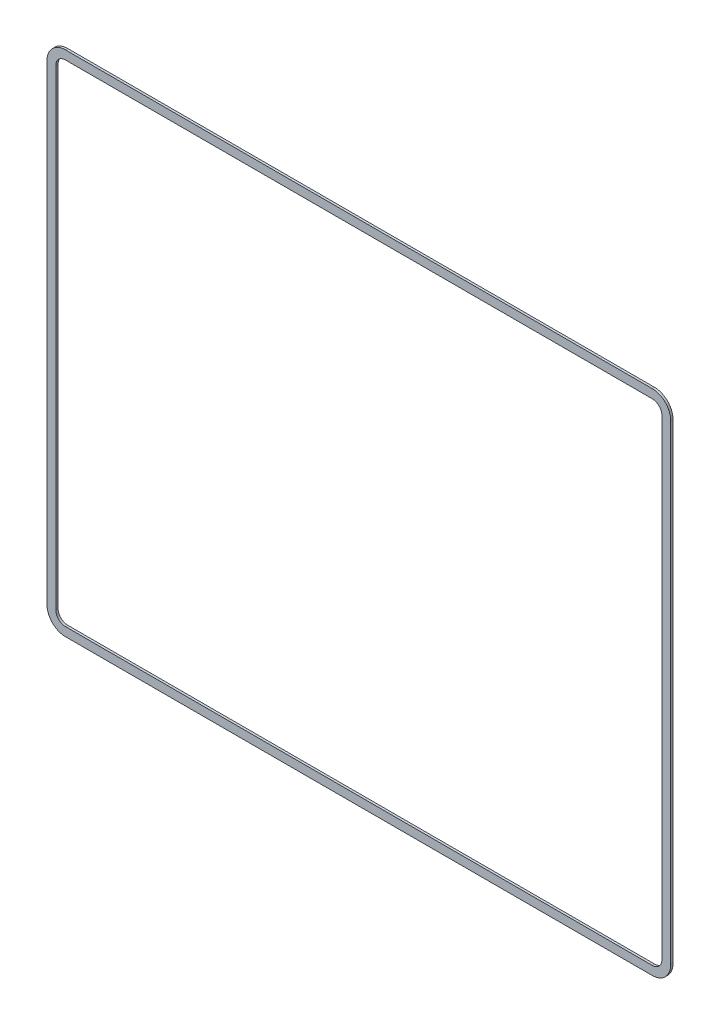
SolidWorks part; units mm, degrees
ref_plane "Front Plane" through (0, 0, 0) normal (0, 0, 1) x (1, 0, 0)
ref_plane "Top Plane" through (0, 0, 0) normal (0, 1, 0) x (1, 0, 0)
ref_plane "Right Plane" through (0, 0, 0) normal (1, 0, 0) x (0, 0, -1)
sketch "Sketch1" plane through (0, 0, 0) normal (0, 0, 1) x (-1, 0, 0)
  line L0 (-79, 0) -> (79, 0) construction
  line L3 (-65.6, 51) -> (-65.6, -51)
  line L4 (-63.5, 55) -> (63.5, 55)
  line L5 (-67.5, 51) -> (-67.5, -51)
  line L6 (-63.5, -55) -> (63.5, -55)
  line L7 (67.5, 51) -> (67.5, -51)
  line L8 (-67.5, 55) -> (67.5, -55) construction
  line L9 (-67.5, -55) -> (67.5, 55) construction
  line L10 (-63.5, -53.1) -> (63.5, -53.1)
  line L11 (65.6, 51) -> (65.6, -51)
  line L12 (-63.5, 53.1) -> (63.5, 53.1)
  arc A0 (63.5, 55) -> (67.5, 51) centre (63.5, 51) cw
  arc A1 (63.5, -55) -> (67.5, -51) centre (63.5, -51) ccw
  arc A2 (-67.5, -51) -> (-63.5, -55) centre (-63.5, -51) ccw
  arc A3 (-63.5, 55) -> (-67.5, 51) centre (-63.5, 51) ccw
  arc A4 (-65.6, -51) -> (-63.5, -53.1) centre (-63.5, -51) ccw
  arc A5 (63.5, -53.1) -> (65.6, -51) centre (63.5, -51) ccw
  arc A6 (63.5, 53.1) -> (65.6, 51) centre (63.5, 51) cw
  arc A7 (-63.5, 53.1) -> (-65.6, 51) centre (-63.5, 51) ccw
  point P6 (0, 0)
  dimension "D3" = 4
  dimension "D1" = 110
  dimension "D2" = 135
  dimension "D4" = 1.9
extrude "Boss-Extrude1" add sketch "Sketch1" along normal blind 0.5 contours L11 A5 L10 A4 L3 A7 L12 A6
